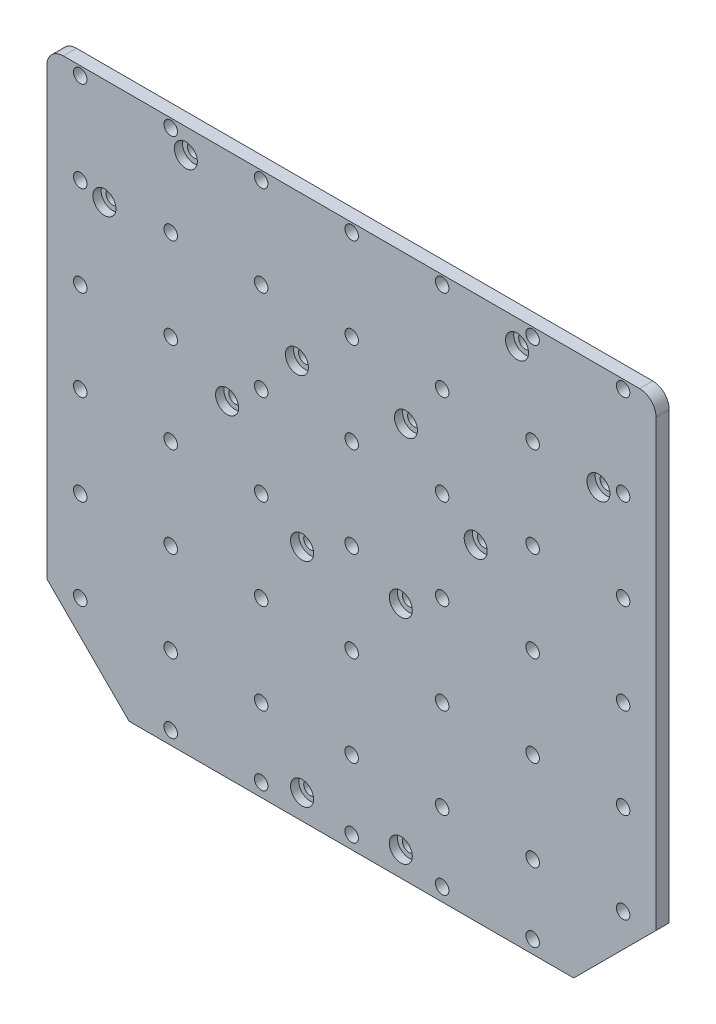
SolidWorks part; units mm, degrees
ref_plane "Plan de face" through (0, 0, 0) normal (0, 0, 1) x (1, 0, 0)
ref_plane "Plan de dessus" through (0, 0, 0) normal (0, 1, 0) x (1, 0, 0)
ref_plane "Plan de droite" through (0, 0, 0) normal (1, 0, 0) x (0, 0, -1)
sketch "Esquisse2" plane through (0, 0, 0) normal (0, 0, 1) x (1, 0, 0)
  line L0 (-225.15, 416.15) -> (225.15, 416.15) construction
  line L1 (-185.15, 25.85) -> (185.15, 25.85)
  line L2 (-185.15, 25.85) -> (-185.15, 356.15)
  line L3 (-185.15, 356.15) -> (185.15, 356.15)
  line L4 (185.15, 25.85) -> (185.15, 356.15)
  line L5 (225.15, 323.15) -> (225.15, 57.85) construction
  line L6 (-225.15, -34.15) -> (-180.15, -34.15) construction
  line L8 (-225.15, 57.85) -> (-225.15, 323.15) construction
  dimension "D1" = 40
  dimension "D2" = 40
  dimension "D3" = 60
  dimension "D4" = 60
extrude "Boss.-Extru.1" add sketch "Esquisse2" along normal blind 8
fillet "Congé1" radius 10 2 edges at (-185.15, 356.15, 4) (185.15, 356.15, 4)
chamfer "Chanfrein1" distance 50 angle 45 2 edges at (-185.15, 25.85, 4) (185.15, 25.85, 4)
sketch "Esquisse4" plane through (0, 0, 8) normal (0, 0, 1) x (1, 0, 0)
  line L0 (50, -15) -> (50, 170.2893) construction
  line L1 (-135.15, 25.85) -> (135.15, 25.85) construction
  line L2 (0, 280.7107) -> (0, 25.85) construction
  line L3 (19, 280.7107) -> (-19, 280.7107) construction
  line L4 (0, 191) -> (-165.15, 356.15) construction
  line L5 (-211.3632, 331.6525) -> (-50, 170.2893) construction
  line L6 (-47.2197, 308.9303) -> (-117.9303, 238.2197) construction
  line L7 (-140.6525, 402.3632) -> (-19, 280.7107) construction
  line L8 (0, 191) -> (165.15, 356.15) construction
  line L9 (175.15, 356.15) -> (-175.15, 356.15) construction
  line L10 (50, 170.2893) -> (-50, 170.2893) construction
  line L11 (-19, 280.7107) -> (-89.7107, 210) construction
  line L12 (19, 280.7107) -> (89.7107, 210) construction
  line L13 (211.3632, 331.6525) -> (50, 170.2893) construction
  circle A0 centre (30, 170.2893) radius 4
  circle A1 centre (-30, 170.2893) radius 4
  circle A2 centre (-33.1421, 266.5685) radius 4
  circle A3 centre (-75.5685, 224.1421) radius 4
  circle A4 centre (33.1421, 266.5685) radius 4
  circle A5 centre (75.5685, 224.1421) radius 4
  circle A6 centre (30, 40.85) radius 4
  circle A7 centre (-30, 40.85) radius 4
  circle A8 centre (-100.6525, 341.15) radius 4
  circle A9 centre (-150.15, 291.6525) radius 4
  circle A10 centre (100.6525, 341.15) radius 4
  circle A11 centre (150.15, 291.6525) radius 4
  point P20 (-82.575, 273.575)
  dimension "D1" = 20
  dimension "D2" = 76.8701
  dimension "D3" = 8
  dimension "D4" = 20
  dimension "D5" = 8
  dimension "D6" = 8
  dimension "D7" = 20
  dimension "D9" = 8
  dimension "D10" = 15
  dimension "D11" = 20
  dimension "D12" = 15
  dimension "D13" = 8
  dimension "D14" = 15
  dimension "D8" = 76.8701
extrude "Enlèv. mat.-Extru.1" cut sketch "Esquisse4" against normal blind 10
sketch "Esquisse5" plane through (0, 0, 8) normal (0, 0, 1) x (1, 0, 0)
  circle A133 centre (30, 40.85) radius 7
  circle A134 centre (30, 40.85) radius 7
  circle A136 centre (-30, 40.85) radius 7
  circle A137 centre (-30, 40.85) radius 7
  circle A139 centre (30, 170.2893) radius 7
  circle A140 centre (30, 170.2893) radius 7
  circle A142 centre (-30, 170.2893) radius 7
  circle A143 centre (-30, 170.2893) radius 7
  circle A145 centre (75.5685, 224.1421) radius 7
  circle A146 centre (75.5685, 224.1421) radius 7
  circle A148 centre (33.1421, 266.5685) radius 7
  circle A149 centre (33.1421, 266.5685) radius 7
  circle A151 centre (150.15, 291.6525) radius 7
  circle A152 centre (150.15, 291.6525) radius 7
  circle A154 centre (100.6525, 341.15) radius 7
  circle A155 centre (100.6525, 341.15) radius 7
  circle A157 centre (-33.1421, 266.5685) radius 7
  circle A158 centre (-33.1421, 266.5685) radius 7
  circle A160 centre (-75.5685, 224.1421) radius 7
  circle A161 centre (-75.5685, 224.1421) radius 7
  circle A163 centre (-150.15, 291.6525) radius 7
  circle A164 centre (-150.15, 291.6525) radius 7
  circle A166 centre (-100.6525, 341.15) radius 7
  circle A167 centre (-100.6525, 341.15) radius 7
  dimension "D1" = 3
  dimension "D2" = 3
  dimension "D3" = 3
  dimension "D4" = 3
  dimension "D5" = 3
  dimension "D6" = 3
  dimension "D7" = 3
  dimension "D8" = 3
  dimension "D9" = 3
  dimension "D10" = 3
  dimension "D11" = 3
  dimension "D12" = 3
extrude "Enlèv. mat.-Extru.2" cut sketch "Esquisse5" against normal blind 5
ref_plane "Plan1" through (-185.15, 75.85, 8) normal (0.7071, -0.7071, 0) x (-0.7071, -0.7071, 0)
sketch "Esquisse6" plane through (0, 0, 8) normal (0, 0, 1) x (1, 0, 0)
  line L0 (-135.15, 25.85) -> (135.15, 25.85) construction
  line L1 (185.15, 75.85) -> (185.15, 346.15) construction
  circle A0 centre (165.15, 75.85) radius 4.1
  circle A1 centre (110.15, 75.85) radius 4.1
  circle A2 centre (55.15, 75.85) radius 4.1
  circle A3 centre (0.15, 75.85) radius 4.1
  circle A4 centre (-54.85, 75.85) radius 4.1
  circle A5 centre (-109.85, 75.85) radius 4.1
  circle A6 centre (-164.85, 75.85) radius 4.1
  circle A7 centre (110.15, 130.85) radius 4.1
  circle A8 centre (55.15, 130.85) radius 4.1
  circle A9 centre (0.15, 130.85) radius 4.1
  circle A10 centre (-54.85, 130.85) radius 4.1
  circle A11 centre (-109.85, 130.85) radius 4.1
  circle A12 centre (-164.85, 130.85) radius 4.1
  circle A13 centre (110.15, 185.85) radius 4.1
  circle A14 centre (55.15, 185.85) radius 4.1
  circle A15 centre (0.15, 185.85) radius 4.1
  circle A16 centre (-54.85, 185.85) radius 4.1
  circle A17 centre (-109.85, 185.85) radius 4.1
  circle A18 centre (-164.85, 185.85) radius 4.1
  circle A19 centre (110.15, 240.85) radius 4.1
  circle A20 centre (55.15, 240.85) radius 4.1
  circle A21 centre (0.15, 240.85) radius 4.1
  circle A22 centre (-54.85, 240.85) radius 4.1
  circle A23 centre (-109.85, 240.85) radius 4.1
  circle A24 centre (-164.85, 240.85) radius 4.1
  circle A25 centre (110.15, 295.85) radius 4.1
  circle A26 centre (55.15, 295.85) radius 4.1
  circle A27 centre (0.15, 295.85) radius 4.1
  circle A28 centre (-54.85, 295.85) radius 4.1
  circle A29 centre (-109.85, 295.85) radius 4.1
  circle A30 centre (-164.85, 295.85) radius 4.1
  circle A31 centre (110.15, 350.85) radius 4.1
  circle A32 centre (55.15, 350.85) radius 4.1
  circle A33 centre (0.15, 350.85) radius 4.1
  circle A34 centre (-54.85, 350.85) radius 4.1
  circle A35 centre (-109.85, 350.85) radius 4.1
  circle A36 centre (-164.85, 350.85) radius 4.1
  circle A37 centre (165.15, 130.85) radius 4.1
  circle A38 centre (165.15, 185.85) radius 4.1
  circle A39 centre (165.15, 240.85) radius 4.1
  circle A40 centre (165.15, 295.85) radius 4.1
  circle A41 centre (165.15, 350.85) radius 4.1
  circle A42 centre (110.15, 33.85) radius 4.1
  circle A43 centre (55.15, 33.85) radius 4.1
  circle A44 centre (0.15, 33.85) radius 4.1
  circle A45 centre (-54.85, 33.85) radius 4.1
  circle A46 centre (-109.85, 33.85) radius 4.1
  dimension "D1" = 50
  dimension "D2" = 8.2
  dimension "D3" = 20
  dimension "D6" = 8.2
  dimension "D7" = 75
  dimension "D8" = 8
  dimension "D4" = 7
  dimension "D5" = 6
  dimension "D9" = 5
extrude "Enlèv. mat.-Extru.3" cut sketch "Esquisse6" against normal blind 10
